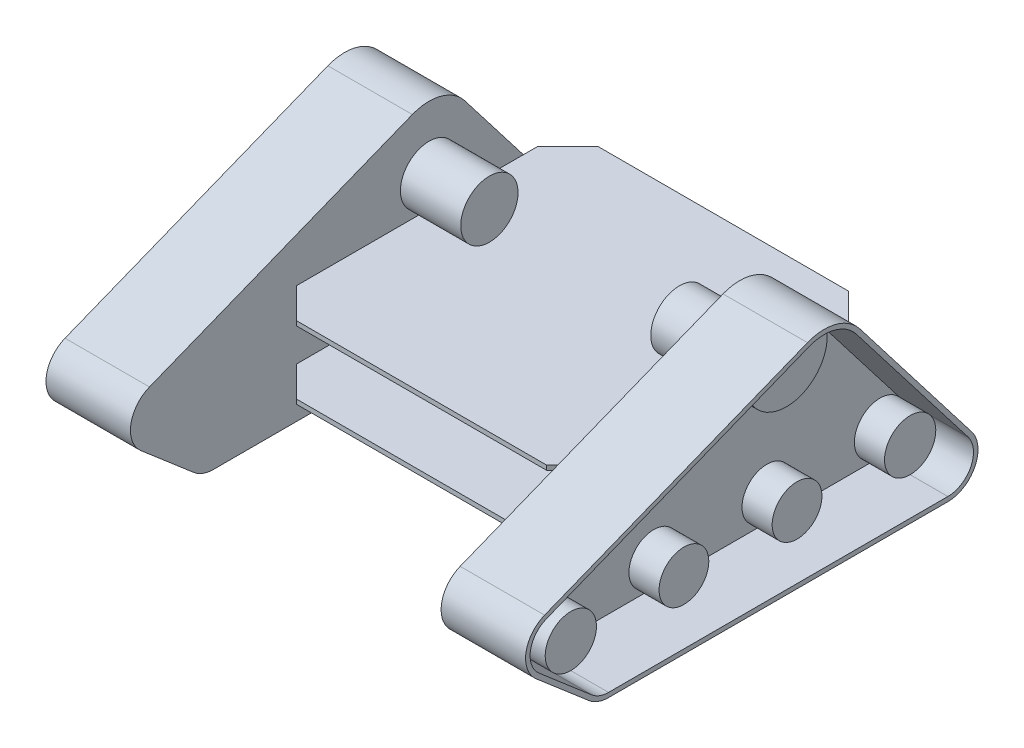
SolidWorks part; units mm, degrees
ref_plane "前视基准面" through (0, 0, 0) normal (0, 0, 1) x (1, 0, 0)
ref_plane "上视基准面" through (0, 0, 0) normal (0, 1, 0) x (1, 0, 0)
ref_plane "右视基准面" through (0, 0, 0) normal (1, 0, 0) x (0, 0, -1)
sketch "草图1" plane through (0, 0, 0) normal (1, 0, 0) x (0, 0, -1)
  line L1 (-100, 1.5) -> (100, 1.5)
  line L2 (-100, 1.5) -> (-100, -1.5)
  line L3 (-100, -1.5) -> (100, -1.5)
  line L4 (100, 1.5) -> (100, -1.5)
  line L5 (-100, 1.5) -> (100, -1.5) construction
  line L6 (-100, -1.5) -> (100, 1.5) construction
  line L7 (-100, 43.5) -> (100, 43.5)
  line L8 (-100, 43.5) -> (-100, 46.5)
  line L9 (-100, 46.5) -> (100, 46.5)
  line L10 (100, 43.5) -> (100, 46.5)
  point P0 (0, 0)
  dimension "D1" = 3
  dimension "D2" = 3
  dimension "D3" = 48
  dimension "D4" = 200
  dimension "D5" = 200
extrude "凸台-拉伸1" add sketch "草图1" along normal mid plane 206
chamfer "倒角1" distance 20 angle 45 4 edges at (103, 45, 100) (-103, 45, 100) (-103, 45, -100) (103, 45, -100)
chamfer "倒角2" distance 20 angle 45 4 edges at (103, 0, -100) (-103, 0, -100) (-103, 0, 100) (103, 0, 100)
sketch "草图2" plane through (103, 0, 0) normal (1, 0, 0) x (0, 0, -1)
  line L0 (105.8403, 0.71) -> (31.7604, 96.8151)
  line L1 (-3.0825, 106.3779) -> (-177.3883, 37.0853)
  line L2 (-183.0158, 3.3149) -> (-148.0158, -26.6851)
  line L3 (-135, -31.5) -> (90, -31.5)
  line L5 (-80, -1.5) -> (80, -1.5) construction
  arc A0 (31.7604, 96.8151) -> (-3.0825, 106.3779) centre (8, 78.5) ccw
  arc A1 (-183.0158, 3.3149) -> (-177.3883, 37.0853) centre (-170, 18.5) cw
  arc A2 (-148.0158, -26.6851) -> (-135, -31.5) centre (-135, -11.5) ccw
  arc A3 (105.8403, 0.71) -> (90, -31.5) centre (90, -11.5) cw
  dimension "D1" = 30
  dimension "D2" = 110
  dimension "D4" = 20
  dimension "D5" = 20
  dimension "D6" = 20
  dimension "D3" = 30
  dimension "D7" = 260
  dimension "D8" = 10
  dimension "D9" = 108
  dimension "D10" = 50
  dimension "D11" = 35
extrude "凸台-拉伸2" add sketch "草图2" along normal blind 3
sketch "草图3" plane through (-103, 0, 0) normal (-1, 0, 0) x (0, 0, 1)
  line L0 (-105.8403, 0.71) -> (-31.7604, 96.8151)
  line L1 (3.0825, 106.3779) -> (177.3883, 37.0853)
  line L2 (183.0158, 3.3149) -> (148.0158, -26.6851)
  line L3 (135, -31.5) -> (-90, -31.5)
  arc A0 (-31.7604, 96.8151) -> (3.0825, 106.3779) centre (-8, 78.5) cw
  arc A1 (177.3883, 37.0853) -> (183.0158, 3.3149) centre (170, 18.5) cw
  arc A2 (148.0158, -26.6851) -> (135, -31.5) centre (135, -11.5) cw
  arc A3 (-90, -31.5) -> (-105.8403, 0.71) centre (-90, -11.5) cw
extrude "凸台-拉伸3" add sketch "草图3" along normal blind 3
sketch "草图4" plane through (106, 0, 0) normal (1, 0, 0) x (0, 0, -1)
  line L0 (-3.0825, 106.3779) -> (-177.3883, 37.0853)
  line L1 (-183.0158, 3.3149) -> (-148.0158, -26.6851)
  line L2 (-135, -31.5) -> (90, -31.5)
  line L3 (105.8403, 0.71) -> (31.7604, 96.8151)
  arc A0 (-177.3883, 37.0853) -> (-183.0158, 3.3149) centre (-170, 18.5) ccw
  arc A1 (-148.0158, -26.6851) -> (-135, -31.5) centre (-135, -11.5) ccw
  arc A2 (90, -31.5) -> (105.8403, 0.71) centre (90, -11.5) ccw
  arc A3 (31.7604, 96.8151) -> (-3.0825, 106.3779) centre (8, 78.5) ccw
extrude "凸台-拉伸5" add sketch "草图4" along normal blind 53
sketch "草图6" plane through (159, 0, 0) normal (1, 0, 0) x (0, 0, -1)
  line L0 (-176.2801, 34.2975) -> (-1.9742, 103.5901)
  line L1 (-181.0635, 5.5926) -> (-146.0635, -24.4074)
  line L2 (-135, -28.5) -> (90, -28.5)
  line L3 (103.4642, -1.1215) -> (29.3844, 94.9836)
  line L4 (-3.0825, 106.3779) -> (-177.3883, 37.0853) construction
  line L5 (105.8403, 0.71) -> (31.7604, 96.8151) construction
  line L6 (-135, -31.5) -> (90, -31.5) construction
  line L7 (-183.0158, 3.3149) -> (-148.0158, -26.6851) construction
  arc A0 (-176.2801, 34.2975) -> (-181.0635, 5.5926) centre (-170, 18.5) ccw
  arc A1 (29.3844, 94.9836) -> (-1.9742, 103.5901) centre (8, 78.5) ccw
  arc A2 (103.4642, -1.1215) -> (90, -28.5) centre (90, -11.5) cw
  arc A3 (-146.0635, -24.4074) -> (-135, -28.5) centre (-135, -11.5) ccw
  dimension "D1" = 3
  dimension "D2" = 3
  dimension "D3" = 3
  dimension "D4" = 3
extrude "切除-拉伸1" cut sketch "草图6" against normal blind 45
sketch "草图8" plane through (-106, 0, 0) normal (-1, 0, 0) x (0, 0, 1)
  line L0 (-31.7604, 96.8151) -> (-105.8403, 0.71)
  line L1 (-90, -31.5) -> (135, -31.5)
  line L2 (148.0158, -26.6851) -> (183.0158, 3.3149)
  line L3 (177.3883, 37.0853) -> (3.0825, 106.3779)
  arc A0 (-105.8403, 0.71) -> (-90, -31.5) centre (-90, -11.5) ccw
  arc A1 (135, -31.5) -> (148.0158, -26.6851) centre (135, -11.5) ccw
  arc A2 (183.0158, 3.3149) -> (177.3883, 37.0853) centre (170, 18.5) ccw
  arc A3 (3.0825, 106.3779) -> (-31.7604, 96.8151) centre (-8, 78.5) ccw
extrude "凸台-拉伸6" add sketch "草图8" along normal blind 53
sketch "草图9" plane through (-159, 0, 0) normal (-1, 0, 0) x (0, 0, 1)
  line L0 (-29.3844, 94.9836) -> (-103.4642, -1.1215)
  line L1 (-90, -28.5) -> (135, -28.5)
  line L2 (146.0635, -24.4074) -> (181.0635, 5.5926)
  line L3 (176.2801, 34.2975) -> (1.9742, 103.5901)
  arc A0 (-103.4642, -1.1215) -> (-90, -28.5) centre (-90, -11.5) ccw
  arc A1 (135, -28.5) -> (146.0635, -24.4074) centre (135, -11.5) ccw
  arc A2 (181.0635, 5.5926) -> (176.2801, 34.2975) centre (170, 18.5) ccw
  arc A3 (1.9742, 103.5901) -> (-29.3844, 94.9836) centre (-8, 78.5) ccw
extrude "切除-拉伸3" cut sketch "草图9" against normal blind 45
sketch "草图10" plane through (114, 0, 0) normal (1, 0, 0) x (0, 0, -1)
  circle A0 centre (8, 78.5) radius 27
  circle A1 centre (-170, 18.5) radius 17
  circle A2 centre (-135, -11.5) radius 17
  circle A3 centre (-60, -11.5) radius 16.5
  circle A4 centre (15, -11.5) radius 16.5
  circle A5 centre (90, -11.5) radius 17
  dimension "D1" = 75
  dimension "D2" = 75
  dimension "D3" = 33
  dimension "D4" = 33
extrude "凸台-拉伸8" add sketch "草图10" along normal blind 20
sketch "草图11" plane through (-114, 0, 0) normal (-1, 0, 0) x (0, 0, 1)
  circle A0 centre (-8, 78.5) radius 27
  circle A1 centre (-90, -11.5) radius 17
  circle A2 centre (-15, -11.5) radius 16.5
  circle A3 centre (60, -11.5) radius 16.5
  circle A4 centre (135, -11.5) radius 17
  circle A5 centre (170, 18.5) radius 17
extrude "凸台-拉伸9" add sketch "草图11" along normal blind 20
sketch "草图12" plane through (103, 0, 0) normal (-1, 0, 0) x (0, 0, 1)
  line L0 (80, 46.5) -> (-70.5444, 46.5) construction
  circle A0 centre (-8, 66.5) radius 19
  dimension "D1" = 38
  dimension "D2" = 20
extrude "凸台-拉伸10" add sketch "草图12" along normal blind 40
sketch "草图13" plane through (-103, 0, 0) normal (1, 0, 0) x (0, 0, -1)
  line L0 (70.5444, 46.5) -> (-80, 46.5) construction
  circle A0 centre (8, 66.5) radius 19
  dimension "D1" = 38
  dimension "D2" = 20
extrude "凸台-拉伸11" add sketch "草图13" along normal blind 40
